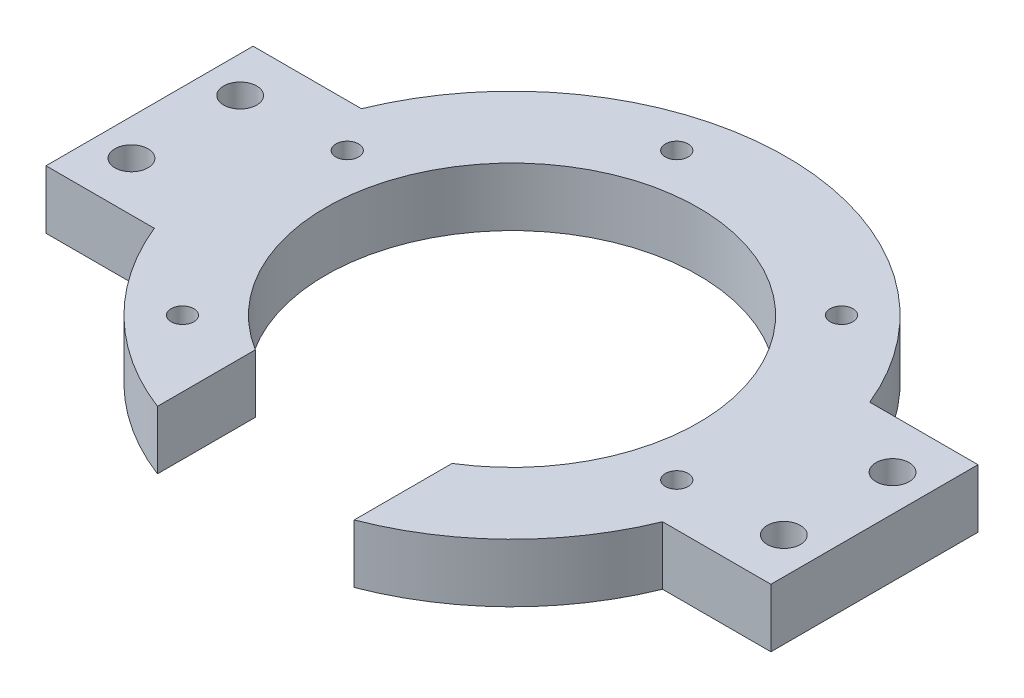
SolidWorks part; units mm, degrees
ref_plane "Front Plane" through (0, 0, 0) normal (0, 0, 1) x (1, 0, 0)
ref_plane "Top Plane" through (0, 0, 0) normal (0, 1, 0) x (1, 0, 0)
ref_plane "Right Plane" through (0, 0, 0) normal (1, 0, 0) x (0, 0, -1)
sketch "Sketch1" plane through (0, 0, 0) normal (1, 0, 0) x (0, 0, -1)
  line L0 (0, 28.5928) -> (0, -29.3105) construction
  line L1 (0, 0) -> (53, 0)
  line L4 (53, 0) -> (53, 11.3)
  line L5 (53, 11.3) -> (0, 11.3)
  line L6 (0, 11.3) -> (0, 0)
  dimension "D2" = 11.3
  dimension "D4" = 53
revolve "Revolve1" add sketch "Sketch1" angle 360 about L0
sketch "Sketch2" plane through (0, 11.3, 0) normal (0, 1, 0) x (1, 0, 0)
  circle A0 centre (0, 0) radius 36
  dimension "D1" = 72
extrude "Cut-Extrude1" cut sketch "Sketch2" against normal blind 11.3
ref_plane "Plane1" through (0, 0, 53) normal (0, 0, 1) x (1, 0, 0)
sketch "Sketch3" plane through (0, 0, 53) normal (0, 0, 1) x (1, 0, 0)
  line L0 (53, 11.3) -> (-53, 11.3) construction
  line L1 (-19, 11.3) -> (19, 11.3)
  line L2 (-19, 11.3) -> (-19, 0)
  line L3 (-19, 0) -> (19, 0)
  line L4 (19, 11.3) -> (19, 0)
  line L5 (-53, 0) -> (53, 0) construction
  line L6 (0, 0) -> (0, 40.8622) construction
  point P11 (0, 11.3)
  dimension "D1" = 38
  dimension "D2" = 11.3
extrude "Cut-Extrude2" cut sketch "Sketch3" against normal blind 41.3
sketch "Sketch4" plane through (0, 11.3, 0) normal (0, 1, 0) x (1, 0, 0)
  line L0 (0, 65.2427) -> (0, -82.2663) construction
  line L1 (13.7174, -51.1941) -> (-13.7174, 51.1941) construction
  circle A0 centre (0, 0) radius 53 construction
  circle A1 centre (0, 0) radius 53 construction
  dimension "D1" = 15
sketch "Sketch5" plane through (0, 11.3, 0) normal (0, 1, 0) x (1, 0, 0)
  line L0 (13.7174, -51.1941) -> (-13.7174, 51.1941) construction
  line L1 (11.6469, -43.4667) -> (-11.6469, 43.4667) construction
  circle A0 centre (11.6469, -43.4667) radius 2.2
  circle A1 centre (-11.6469, 43.4667) radius 2.2
  point P6 (0, 0)
  dimension "D1" = 4.4
  dimension "D2" = 4.4
  dimension "D3" = 90
extrude "Cut-Extrude3" cut sketch "Sketch5" against normal through all
pattern_circular "CirPattern1" count 3 over 360 about axis through (0, 0, 0) along (0, 1, 0) of "Cut-Extrude3"
ref_plane "Plane2" through (53, 0, 0) normal (1, 0, 0) x (0, 0, -1)
sketch "Sketch6" plane through (53, 0, 0) normal (1, 0, 0) x (0, 0, -1)
  line L0 (-49.4773, 0) -> (53, 0) construction
  line L1 (-20, 0) -> (20, 0)
  line L2 (-20, 0) -> (-20, 11.3)
  line L3 (-20, 11.3) -> (20, 11.3)
  line L4 (20, 0) -> (20, 11.3)
  line L5 (36, 11.3) -> (-30.5778, 11.3) construction
  point P8 (0, 0)
  dimension "D1" = 40
extrude "Boss-Extrude1" add sketch "Sketch6" against normal blind 5 and the other way blind 17
mirror "Mirror1" about plane through (0, 0, 0) normal (1, 0, 0) of "Boss-Extrude1"
sketch "Sketch7" plane through (0, 11.3, 0) normal (0, 1, 0) x (1, 0, 0)
  line L2 (55, 20) -> (55, -20) construction
  line L3 (63, 20) -> (63, -20) construction
  line L4 (70, 20) -> (49.0816, 20) construction
  line L5 (70, -20) -> (49.0816, -20) construction
  circle A0 centre (63, 10.5) radius 3.2
  circle A1 centre (0, 0) radius 55 construction
  point P15 (55, 0)
  dimension "D2" = 6.4
  dimension "D4" = 110
  dimension "D1" = 8
  dimension "D3" = 9.5
extrude "Cut-Extrude4" cut sketch "Sketch7" against normal through all
mirror "Mirror2" about plane through (0, 0, 0) normal (1, 0, 0) of "Cut-Extrude4" second plane through (0, 0, 0) second plane normal (0, 0, 1)
sketch "Sketch8" [suppressed] plane through (0, 11.3, 0) normal (0, 1, 0) x (1, 0, 0)
  line L0 (0, 58.4063) -> (0, -54.2007) construction
  line L1 (-63, 13.7) -> (-63, -13.7) construction
  line L2 (-63, 0) -> (34.2196, 0) construction
  line L3 (-66.2, 10.5) -> (-59.8, 10.5) construction
  line L4 (19, -49.4773) -> (19, 0) construction
  line L5 (19, -30.5778) -> (-19, -30.5778) construction
  circle A0 centre (-63, 10.5) radius 3.2 construction
  circle A1 centre (-63, -10.5) radius 3.2 construction
